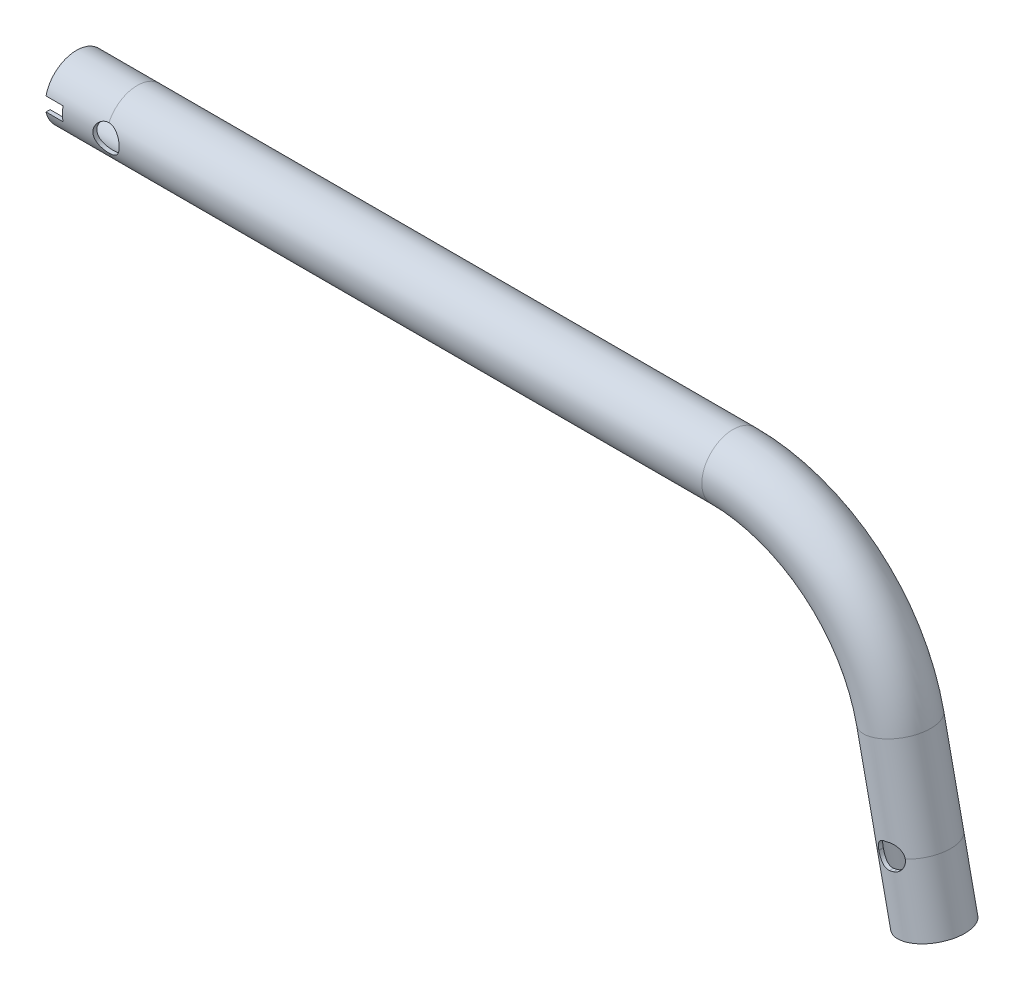
SolidWorks part; units mm, degrees
ref_plane "Front Plane" through (0, 0, 0) normal (0, 0, 1) x (1, 0, 0)
ref_plane "Top Plane" through (0, 0, 0) normal (0, 1, 0) x (1, 0, 0)
ref_plane "Right Plane" through (0, 0, 0) normal (1, 0, 0) x (0, 0, -1)
sketch "Sketch1" plane through (0, 0, 0) normal (0, 0, 1) x (1, 0, 0)
  line L0 (0, 0) -> (181.2548, 0)
  line L1 (232.1185, -41.1886) -> (238.2, -69.8)
  line L2 (0, 0) -> (-18.5064, 0)
  line L3 (238.2, -69.8) -> (242.4936, -90)
  arc A0 (232.1185, -41.1886) -> (181.2548, 0) centre (181.2548, -52) ccw
  point P10 (238.2, -69.8)
  dimension "D2" = 52
  dimension "D1" = 78
  dimension "D3" = 238.2
  dimension "D4" = 69.8
  dimension "D5" = 261
  dimension "D6" = 90
ref_plane "Plane1" through (-18.5064, 0, 0) normal (-1, 0, 0) x (0, 0, 1)
sketch "Sketch2" plane through (-18.5064, 0, 0) normal (-1, 0, 0) x (0, 0, 1)
  circle A0 centre (0, 0) radius 9.5
  circle A1 centre (0, 0) radius 8.3
  dimension "D1" = 1.2
sweep "Sweep1" add profiles "Sketch2" path "Sketch1"
sketch "Sketch3" plane through (0, 0, 0) normal (0, 0, 1) x (1, 0, 0)
  line L0 (238.2, -69.8) -> (242.2104, -68.9476) construction
  line L1 (228.9076, -71.7752) -> (247.4924, -67.8248) construction
  line L2 (238.2, -69.8) -> (237.4619, -66.3276) construction
  line L3 (242.2278, -69.0293) -> (242.193, -68.8658)
  line L4 (238.0418, -66.17) -> (236.868, -66.4195)
  line L5 (234.1722, -70.5707) -> (234.207, -70.7342)
  line L6 (238.3582, -73.43) -> (239.532, -73.1805)
  arc A0 (238.3582, -73.43) -> (234.207, -70.7342) centre (237.6305, -70.0065) cw
  arc A1 (239.532, -73.1805) -> (242.2278, -69.0293) centre (238.8043, -69.757) ccw
  arc A2 (242.193, -68.8658) -> (238.0418, -66.17) centre (238.7695, -69.5935) ccw
  arc A3 (236.868, -66.4195) -> (234.1722, -70.5707) centre (237.5957, -69.843) ccw
  point P8 (242.2104, -68.9476)
  point P14 (242.9555, -72.4528)
  point P17 (241.4653, -65.4423)
  point P20 (233.4445, -67.1472)
  dimension "D6" = 3.5
  dimension "D1" = 4.1
  dimension "D2" = 3.55
  dimension "D3" = 90
  dimension "D4" = 7.1671
  dimension "D5" = 8.2
extrude "Cut-Extrude1" cut sketch "Sketch3" against normal up to next and the other way up to next
sketch "Sketch4" plane through (0, 0, 0) normal (0, 0, 1) x (1, 0, 0)
  line L0 (0, -9.5) -> (0, 9.5) construction
  circle A0 centre (0, 0) radius 4
extrude "Cut-Extrude2" cut sketch "Sketch4" along normal up to next
sketch "Sketch5" plane through (0, 0, 0) normal (0, 0, 1) x (1, 0, 0)
  line L0 (-18.5064, 0) -> (-18.5064, 2.1)
  line L1 (-18.5064, 9.5) -> (-18.5064, -9.5) construction
  line L2 (-18.5064, 2.1) -> (-13.3064, 2.1)
  line L3 (-13.3064, 2.1) -> (-13.3064, -2.1)
  line L4 (-13.3064, -2.1) -> (-18.5064, -2.1)
  line L5 (-18.5064, -2.1) -> (-18.5064, 0)
  dimension "D1" = 5.2
  dimension "D2" = 4.2
extrude "Cut-Extrude3" cut sketch "Sketch5" against normal through all and the other way through all
